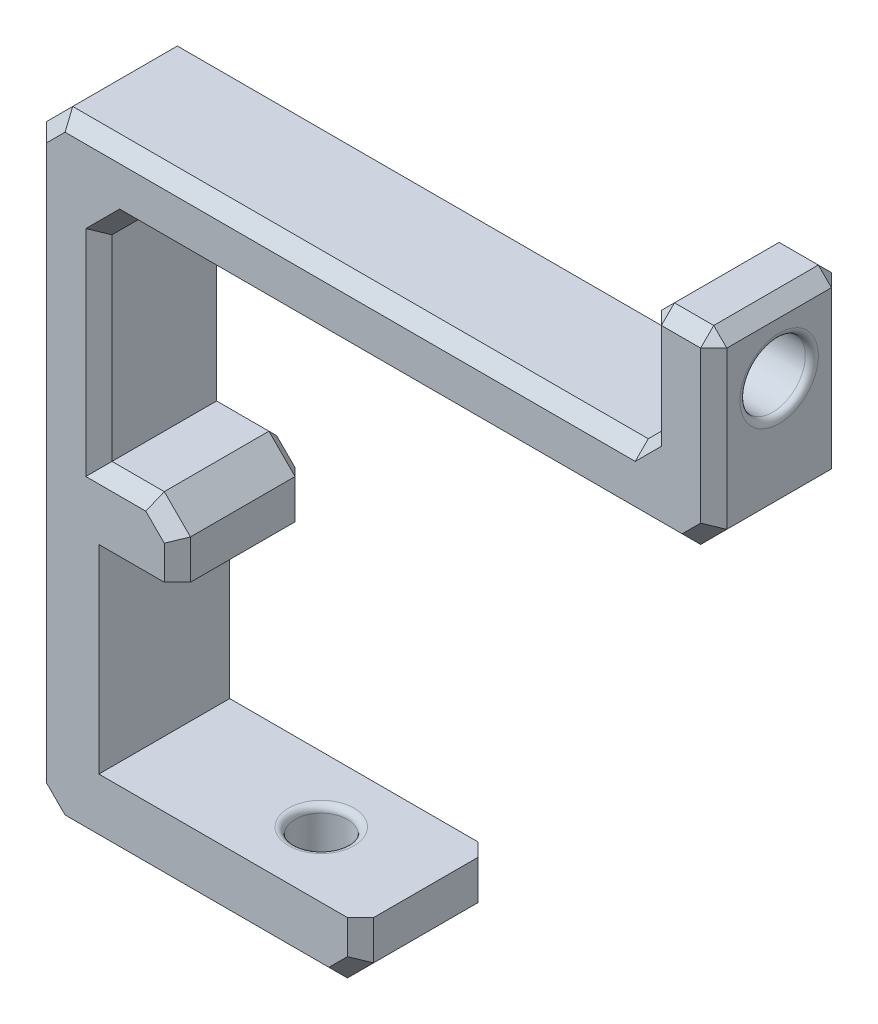
SolidWorks part; units mm, degrees
ref_plane "Plano frontal" through (0, 0, 0) normal (0, 0, 1) x (1, 0, 0)
ref_plane "Plano superior" through (0, 0, 0) normal (0, 1, 0) x (1, 0, 0)
ref_plane "Plano direito" through (0, 0, 0) normal (1, 0, 0) x (0, 0, -1)
sketch "Esboço1" plane through (0, 0, 0) normal (0, 0, 1) x (1, 0, 0)
  line L1 (1.8864, -7.75) -> (-4.1136, -7.75)
  line L2 (-4.1136, 14.25) -> (-4.1136, -2.75)
  line L3 (-4.1136, -22.95) -> (15.8864, -22.95)
  line L4 (15.8864, -22.95) -> (15.8864, -27.95)
  line L5 (15.8864, -27.95) -> (-9.1136, -27.95)
  line L6 (-9.1136, -27.95) -> (-9.1136, 19.25)
  line L7 (1.8864, -2.75) -> (1.8864, -7.75)
  line L8 (1.8864, -2.75) -> (-4.1136, -2.75)
  line L9 (-4.1136, -7.75) -> (-4.1136, -22.95)
  line L18 (-9.1136, 19.25) -> (37.8864, 19.25)
  line L19 (-4.1136, 14.25) -> (42.8864, 14.25)
  line L20 (42.8864, 14.25) -> (42.8864, 29.25)
  line L21 (42.8864, 29.25) -> (37.8864, 29.25)
  line L22 (37.8864, 19.25) -> (37.8864, 29.25)
  dimension "D1" = 5
  dimension "D2" = 20
  dimension "D3" = 15.2
  dimension "D4" = 6
  dimension "D5" = 5
  dimension "D6" = 17
  dimension "D7" = 5
  dimension "D8" = 5
  dimension "D9" = 5
  dimension "D10" = 10
  dimension "D11" = 47
extrude "Ressalto-extrusão1" add sketch "Esboço1" along normal blind 10
sketch "Esboço3" plane through (0, -27.95, 0) normal (0, -1, 0) x (1, 0, 0)
  line L0 (15.8864, 5) -> (7.8864, 5) construction
  line L1 (15.8864, 10) -> (15.8864, 0) construction
  circle A0 centre (7.8864, 5) radius 2
  dimension "D1" = 4
  dimension "D2" = 8
extrude "Corte-extrusão1" cut sketch "Esboço3" against normal blind 15
chamfer "Chanfro1" distance 1.6 angle 45 1 edges at (7.8864, -27.95, 3)
fillet "Filete1" radius 0.5 1 edges at (7.8864, -22.95, 3)
chamfer "Chanfro5" distance 2 angle 45 6 edges at (15.8864, -27.95, 5) (-9.1136, -27.95, 5) (1.8864, -2.75, 5) (-9.1136, 19.25, 5) (-4.1136, 14.25, 5) (42.8864, 14.25, 5)
sketch "Esboço4" plane through (37.8864, 0, 0) normal (-1, 0, 0) x (0, 0, 1)
  line L0 (0, 19.25) -> (10, 29.25) construction
  circle A0 centre (5, 24.25) radius 2.5
  dimension "D1" = 5
extrude "Corte-extrusão2" cut sketch "Esboço4" against normal blind 10 contours A0
chamfer "Chanfro8" distance 1 angle 45 37 edges at (1.8864, -6.25, 0) (0.8864, -3.75, 0) (-2.1136, -2.75, 0) (-4.1136, 4.75, 0) (15.8864, -24.45, 0) (14.8864, -26.95, 0) (3.3864, -27.95, 0) (-8.1136, -26.95, 0) (-9.1136, -4.35, 0) (15.8864, -24.45, 10) (14.8864, -26.95, 10) (3.3864, -27.95, 10) (-8.1136, -26.95, 10) (-9.1136, -4.35, 10) (1.8864, -6.25, 10) (0.8864, -3.75, 10) (-2.1136, -2.75, 10) (-4.1136, 4.75, 10) (-3.1136, 13.25, 0) (37.8864, 19.25, 5) (19.3864, 14.25, 0) (41.8864, 15.25, 0) (42.8864, 22.75, 0) (-3.1136, 13.25, 10) (19.3864, 14.25, 10) (41.8864, 15.25, 10) (42.8864, 22.75, 10) (42.8864, 29.25, 5) (40.3864, 29.25, 10) (-8.1136, 18.25, 10) (15.3864, 19.25, 10) (37.8864, 24.25, 10) (37.8864, 29.25, 5) (37.8864, 24.25, 0) (15.3864, 19.25, 0) (-8.1136, 18.25, 0) (40.3864, 29.25, 0)
fillet "Filete2" radius 0.5 2 edges at (42.8864, 24.25, 7.5) (37.8864, 24.25, 7.5)
